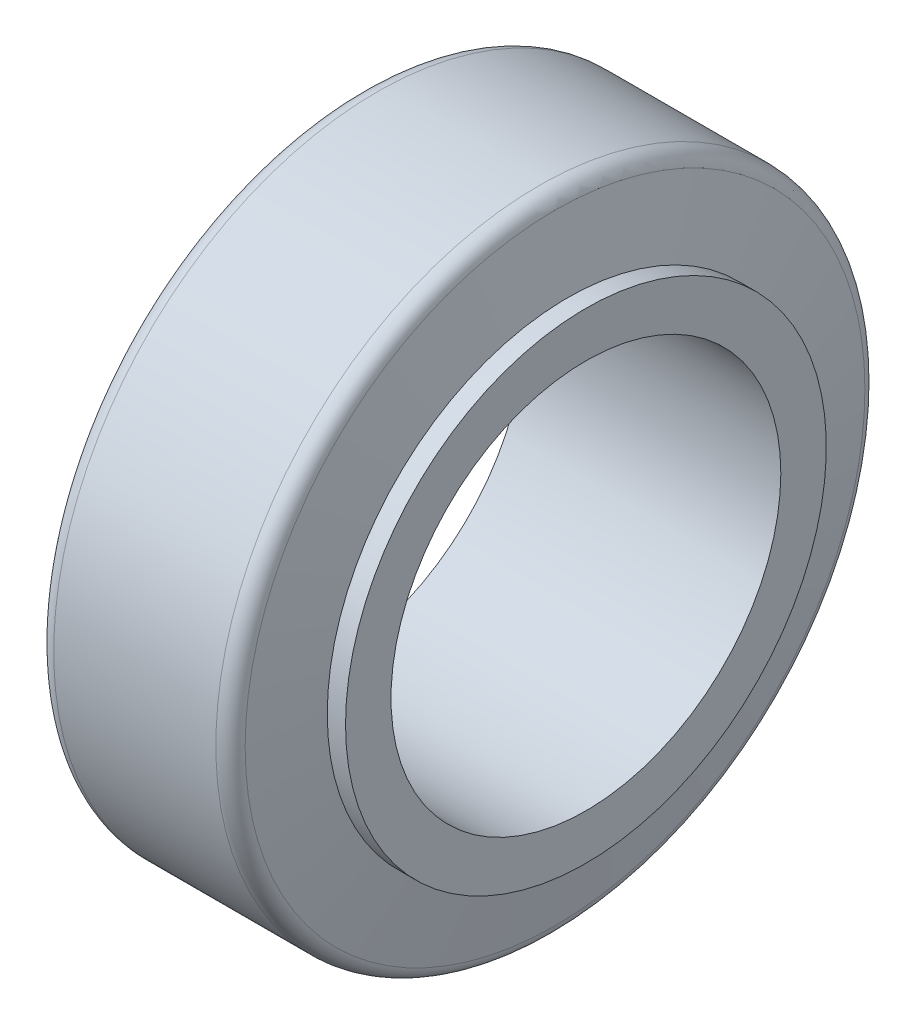
SolidWorks part; units mm, degrees
material "PUR"
ref_plane "Front Plane" through (0, 0, 0) normal (0, 0, 1) x (1, 0, 0)
ref_plane "Top Plane" through (0, 0, 0) normal (0, 1, 0) x (1, 0, 0)
ref_plane "Right Plane" through (0, 0, 0) normal (1, 0, 0) x (0, 0, -1)
sketch "Sketch1" plane through (0, 0, 0) normal (0, 0, 1) x (1, 0, 0)
  line L0 (-11.65, -39.8) -> (11.65, -39.8)
  line L1 (-11.65, -39.8) -> (-13.5, -29.6)
  line L2 (15.75, -23.6) -> (4.25, -20.75)
  line L3 (4.25, -20.75) -> (4.25, -17)
  line L4 (4.25, -17) -> (20.15, -15.75)
  line L5 (20.15, -15.75) -> (20.15, -10.05)
  line L6 (0, -39.8) -> (0, 0) construction
  line L7 (0, 0) -> (22.2, 0) construction
  line L8 (20.15, -10.05) -> (-20.15, -10.05)
  line L9 (-20.15, -15.75) -> (-20.15, -10.05)
  line L10 (-4.25, -17) -> (-20.15, -15.75)
  line L11 (-4.25, -20.75) -> (-4.25, -17)
  line L12 (-15.75, -23.6) -> (-4.25, -20.75)
  line L13 (-13.5, -29.6) -> (-15.75, -29.6)
  line L14 (-15.75, -29.6) -> (-15.75, -23.6)
  line L15 (11.65, -39.8) -> (13.5, -29.6)
  line L16 (13.5, -29.6) -> (15.75, -29.6)
  line L17 (15.75, -29.6) -> (15.75, -23.6)
  point P12 (0, -10.05)
  dimension "D1" = 40.3
  dimension "D2" = 31.5
  dimension "D3" = 20.1
  dimension "D4" = 31.5
  dimension "D5" = 79.6
  dimension "D6" = 6
  dimension "D7" = 15.9
  dimension "D8" = 23.3
  dimension "D9" = 27
  dimension "D10" = 47.2
  dimension "D11" = 41.5
  dimension "D12" = 34
revolve "Revolve1" add sketch "Sketch1" angle 360 about L7
fillet "Fillet1" radius 2 8 edges at (4.25, 0, 20.75) (4.25, 0, 17) (-4.25, 0, 17) (-4.25, 0, 20.75) (20.15, 0, 15.75) (-20.15, 0, 15.75) (-11.65, 0, 39.8) (11.65, 0, 39.8)
sketch "Sketch2" plane through (20.15, 0, 0) normal (1, 0, 0) x (0, 0, -1)
  circle A0 centre (0, 0) radius 24
  dimension "D1" = 48
extrude "Cut-Extrude1" cut sketch "Sketch2" against normal through all
move or copy body "Body-Move/Copy1" [suppressed] bodies to move or copy 101
